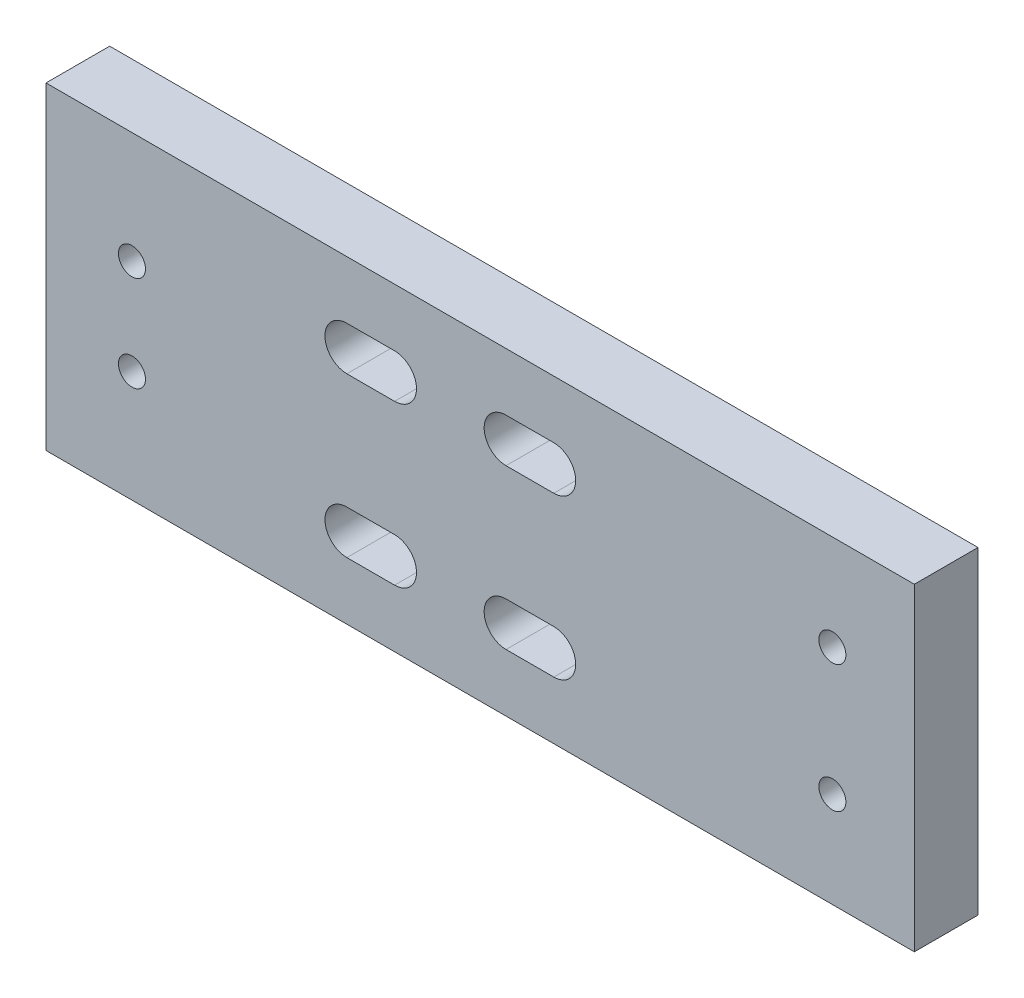
SolidWorks part; units mm, degrees
ref_plane "Front Plane" through (0, 0, 0) normal (0, 0, 1) x (1, 0, 0)
ref_plane "Top Plane" through (0, 0, 0) normal (0, 1, 0) x (1, 0, 0)
ref_plane "Right Plane" through (0, 0, 0) normal (1, 0, 0) x (0, 0, -1)
ref_plane "Plane1" through (0, 0, 238) normal (0, 0, 1) x (1, 0, 0)
sketch "Sketch1" plane through (0, 0, 238) normal (0, 0, 1) x (1, 0, 0)
  line L0 (227.2, 280) -> (336.3, 280)
  line L1 (336.3, 280) -> (336.3, 320)
  line L2 (336.3, 320) -> (227.2, 320)
  line L3 (227.2, 320) -> (227.2, 280)
  line L4 (265, 287.25) -> (271, 287.25)
  line L5 (271, 292.75) -> (265, 292.75)
  line L6 (265, 307.25) -> (271, 307.25)
  line L7 (271, 312.75) -> (265, 312.75)
  line L8 (285, 287.25) -> (291, 287.25)
  line L9 (291, 292.75) -> (285, 292.75)
  line L10 (285, 307.25) -> (291, 307.25)
  line L11 (291, 312.75) -> (285, 312.75)
  arc A0 (271, 287.25) -> (271, 292.75) centre (271, 290) ccw
  arc A1 (265, 292.75) -> (265, 287.25) centre (265, 290) ccw
  arc A2 (271, 307.25) -> (271, 312.75) centre (271, 310) ccw
  arc A3 (265, 312.75) -> (265, 307.25) centre (265, 310) ccw
  arc A4 (291, 287.25) -> (291, 292.75) centre (291, 290) ccw
  arc A5 (285, 292.75) -> (285, 287.25) centre (285, 290) ccw
  arc A6 (291, 307.25) -> (291, 312.75) centre (291, 310) ccw
  arc A7 (285, 312.75) -> (285, 307.25) centre (285, 310) ccw
  circle A8 centre (238, 294) radius 1.7
  circle A9 centre (238, 306) radius 1.7
  circle A10 centre (326, 292) radius 1.7
  circle A11 centre (326, 308) radius 1.7
extrude "Boss-Extrude1" add sketch "Sketch1" along normal blind 8
sketch "Sketch2" plane through (0, 0, 238) normal (0, 0, 1) x (1, 0, 0)
  circle A0 centre (238, 294) radius 3.3
  circle A1 centre (238, 306) radius 3.3
  circle A2 centre (326, 292) radius 3.3
  circle A3 centre (326, 308) radius 3.3
extrude "Cut-Extrude1" cut sketch "Sketch2" along normal blind 3.5
